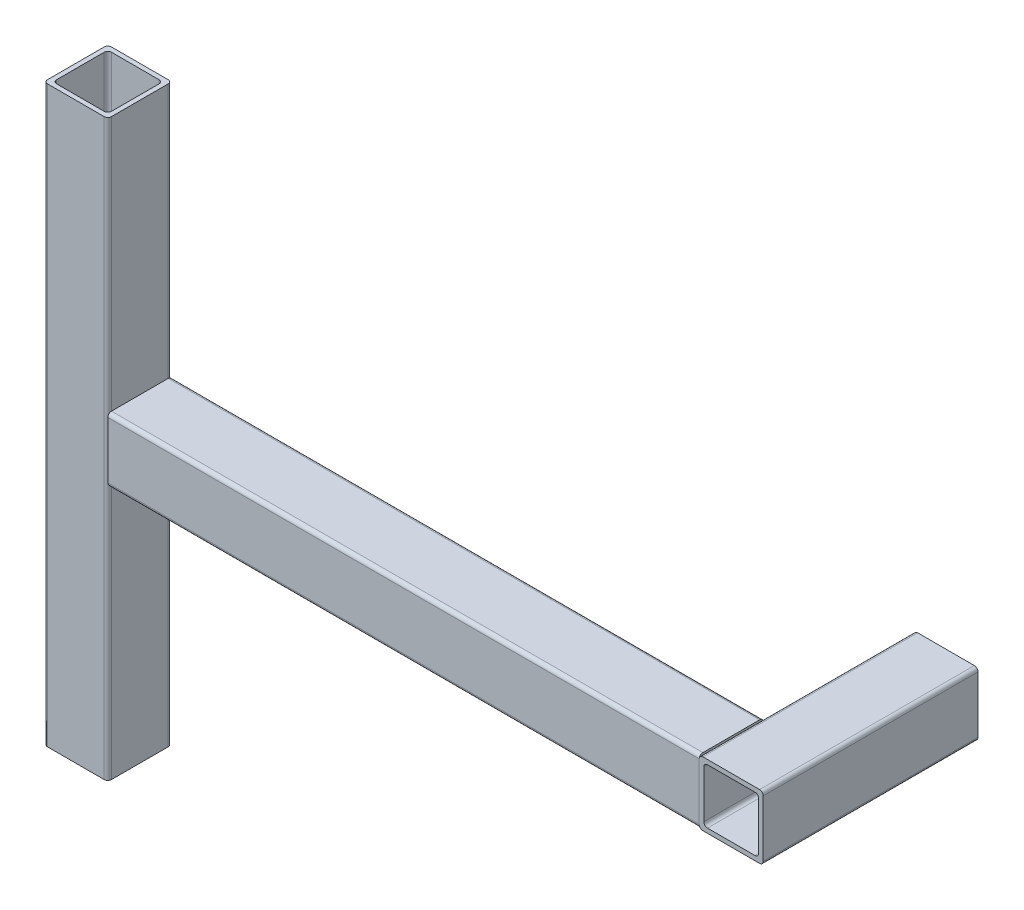
SolidWorks part; units mm, degrees
material "1.0037 (S235JR)"
ref_plane "Plan de face" through (0, 0, 0) normal (0, 0, 1) x (1, 0, 0)
ref_plane "Plan de dessus" through (0, 0, 0) normal (0, 1, 0) x (1, 0, 0)
ref_plane "Plan de droite" through (0, 0, 0) normal (1, 0, 0) x (0, 0, -1)
sketch3d "Esquisse3D1"
  line L0 (0, 0, 0) -> (0, 0, 100)
  line L1 (0, 0, 100) -> (-358.55, 0, 100)
  line L2 (-358.55, -157.055, 100) -> (-358.55, 157.055, 100)
  line L3 (0, 0, 100) -> (0, 232.0766, 100) construction
  point P5 (-358.55, 0, 100)
  dimension "D1" = 100
  dimension "D2" = 314.11
  dimension "D4" = 358.55
other "Custom TUBE-CARRE-35-2.5(1)"
ref_plane "Plan1" through (0, 0, 0) normal (0, 0, 1) x (1, 0, 0)
sketch "Esquisse1" plane through (0, 0, 0) normal (0, 0, 1) x (1, 0, 0)
  line L1 (-13, -15) -> (13, -15)
  line L2 (-15, -13) -> (-15, 13)
  line L3 (-13, 15) -> (13, 15)
  line L4 (15, -13) -> (15, 13)
  line L5 (-15, -15) -> (15, 15) construction
  line L6 (-15, 15) -> (15, -15) construction
  line L7 (-15.5, -17.5) -> (15.5, -17.5)
  line L8 (-17.5, -15.5) -> (-17.5, 15.5)
  line L9 (-15.5, 17.5) -> (15.5, 17.5)
  line L10 (17.5, -15.5) -> (17.5, 15.5)
  line L11 (-17.5, -17.5) -> (17.5, 17.5) construction
  line L12 (-17.5, 17.5) -> (17.5, -17.5) construction
  arc A0 (15.5, -17.5) -> (17.5, -15.5) centre (15.5, -15.5) ccw
  arc A1 (13, -15) -> (15, -13) centre (13, -13) ccw
  arc A2 (-13, -15) -> (-15, -13) centre (-13, -13) cw
  arc A3 (-15.5, -17.5) -> (-17.5, -15.5) centre (-15.5, -15.5) cw
  arc A4 (15.5, 17.5) -> (17.5, 15.5) centre (15.5, 15.5) cw
  arc A5 (13, 15) -> (15, 13) centre (13, 13) cw
  arc A6 (-15, 13) -> (-13, 15) centre (-13, 13) cw
  arc A7 (-17.5, 15.5) -> (-15.5, 17.5) centre (-15.5, 15.5) cw
  point P0 (0, 0)
  point P6 (0, 0)
  point P35 (0, 17.5)
  point P36 (0, 15)
  point P37 (-15, 0)
  point P38 (-17.5, 0)
  point P39 (0, -15)
  point P40 (0, -17.5)
  point P41 (15, 0)
  point P42 (17.5, 0)
  point P43 (0, 0)
  dimension "D5" = 2
  dimension "D1" = 2.5
  dimension "D2" = 35
  dimension "D3" = 35
  dimension "D4" = 2.5
